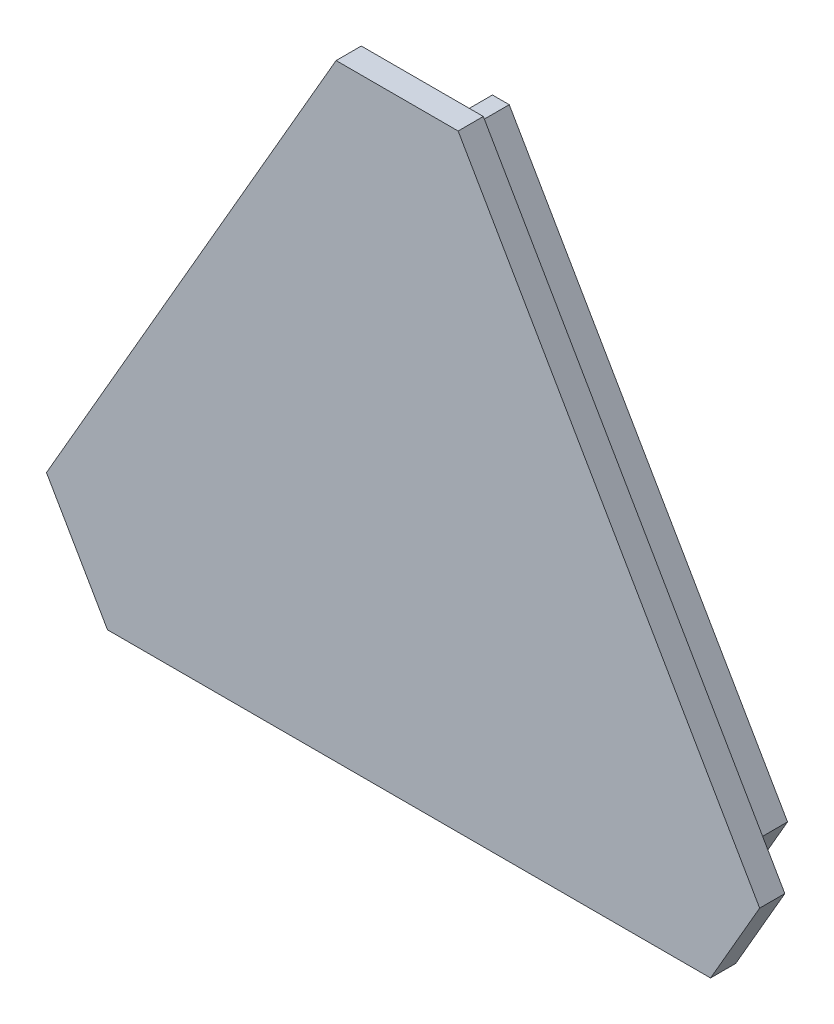
SolidWorks part; units mm, degrees
ref_plane "Front Plane" through (0, 0, 0) normal (0, 0, 1) x (1, 0, 0)
ref_plane "Top Plane" through (0, 0, 0) normal (0, 1, 0) x (1, 0, 0)
ref_plane "Right Plane" through (0, 0, 0) normal (1, 0, 0) x (0, 0, -1)
sketch "Sketch2" plane through (0, 0, 297.1478) normal (0, 0, 1) x (1, 0, 0)
  line L0 (222.116, -44.1065) -> (277.385, -139.8353)
  line L1 (277.385, -139.8353) -> (270.116, -152.4257)
  line L2 (270.116, -152.4257) -> (159.5778, -152.4257)
  line L3 (222.3469, -43.7065) -> (277.8469, -139.8353) construction
  line L4 (277.8469, -139.8353) -> (270.3469, -152.8257) construction
  line L5 (270.3469, -152.8257) -> (159.3469, -152.8257) construction
  line L7 (159.5778, -152.4257) -> (157.9091, -149.5353)
  line L8 (157.9091, -149.5353) -> (159.1271, -147.4257)
  line L9 (159.3469, -152.8257) -> (157.4472, -149.5353) construction
  line L10 (172.6723, -123.1646) -> (157.4472, -149.5353) construction
  line L11 (159.1271, -147.4257) -> (267.2292, -147.4257)
  line L12 (267.2292, -147.4257) -> (271.6115, -139.8353)
  line L13 (271.6115, -139.8353) -> (217.5604, -46.2161)
  line L14 (222.116, -44.1065) -> (218.7784, -44.1065)
  line L15 (218.7784, -44.1065) -> (217.5604, -46.2161)
  line L16 (218.5475, -43.7065) -> (203.3223, -70.0772) construction
  line L17 (218.5475, -43.7065) -> (222.3469, -43.7065) construction
  dimension "D6" = 5
  dimension "D7" = 5
  dimension "D8" = 5
extrude "Boss-Extrude1" add sketch "Sketch2" against normal blind 10
sketch "Sketch3" plane through (0, 0, 297.1478) normal (0, 0, 1) x (1, 0, 0)
  line L0 (202.7281, -38.7065) -> (226.9657, -38.7065)
  line L1 (226.9657, -38.7065) -> (286.8511, -142.431)
  line L2 (286.8511, -142.431) -> (277.0969, -159.3257)
  line L3 (277.0969, -159.3257) -> (157.3262, -159.3257)
  line L4 (157.3262, -159.3257) -> (145.2074, -138.3353)
  line L5 (145.2074, -138.3353) -> (202.7281, -38.7065)
extrude "Boss-Extrude2" add sketch "Sketch3" along normal blind 5
mirror "Mirror1" about plane through (218.7784, -44.1065, 287.1478) normal (0, 0, 1) of bodies 102
delete or keep bodies "Body-Delete1" type delete bodies bodies 102
mirror "Mirror2" about plane through (218.7784, -44.1065, 287.1478) normal (0, 0, -1) of bodies 103
delete or keep bodies "Body-Delete2" type delete bodies bodies 103
equation "\"gap\"= 0.4"
